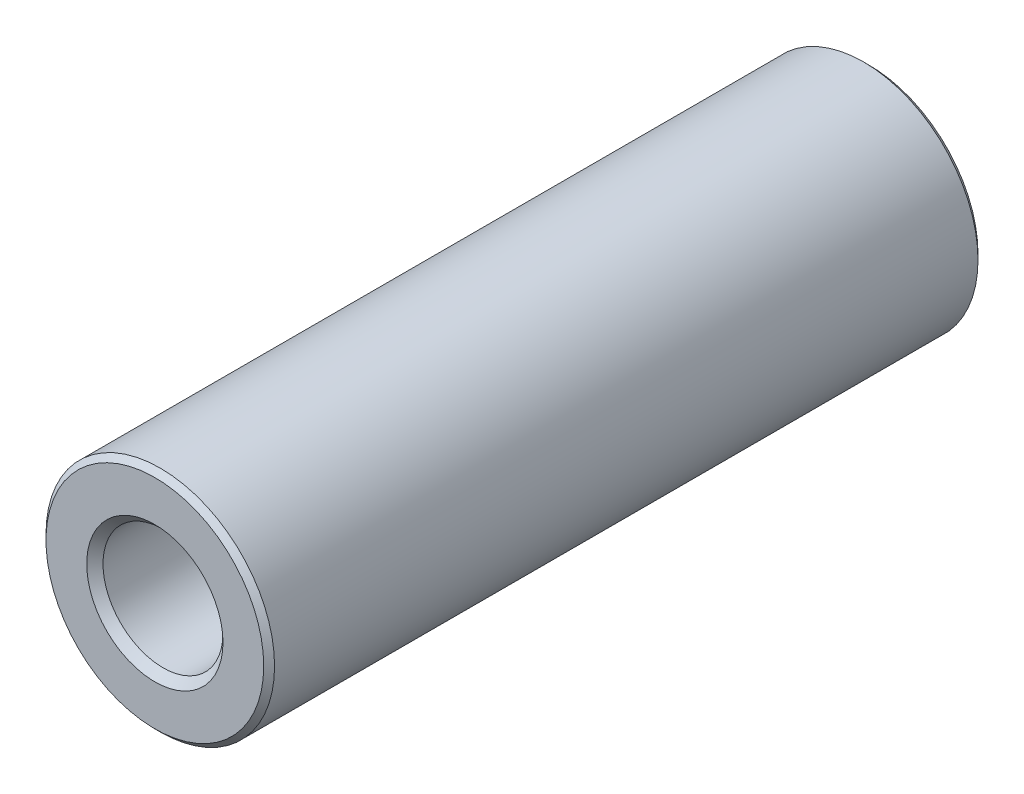
SolidWorks part; units mm, degrees
ref_plane "Front Plane" through (0, 0, 0) normal (0, 0, 1) x (1, 0, 0)
ref_plane "Top Plane" through (0, 0, 0) normal (0, 1, 0) x (1, 0, 0)
ref_plane "Right Plane" through (0, 0, 0) normal (1, 0, 0) x (0, 0, -1)
sketch "Sketch1" plane through (0, 0, 0) normal (0, 0, 1) x (1, 0, 0)
  circle A0 centre (0, 0) radius 4 construction
  circle A1 centre (0, 0) radius 2.1 construction
  point P4 (0, 4)
  dimension "ID" = 4.2
  dimension "OD" = 8
sketch "Sketch2" plane through (0, 0, 0) normal (1, 0, 0) x (0, 0, -1)
  line L0 (-12.5, 4) -> (12.5, 4) construction
  dimension "Length" = 25
sketch "Sketch3" plane through (0, 0, 0) normal (0, 0, 1) x (1, 0, 0)
  circle A0 centre (0, 0) radius 2.1 construction
  circle A1 centre (0, 0) radius 4 construction
  circle A2 centre (0, 0) radius 2.1
  circle A3 centre (0, 0) radius 4
extrude "Boss-Extrude1" add sketch "Sketch3" against normal up to vertex (12.5 mm away) and the other way up to vertex (12.5 mm away) up to point (0, 4, -12.5) other way up to point (0, 4, 12.5)
chamfer "Chamfer1" distance 0.19 angle 45 2 edges at (4, 0, 12.5) (4, 0, -12.5)
chamfer "Chamfer2" distance 0.285 angle 45 2 edges at (2.1, 0, 12.5) (2.1, 0, -12.5)
equation "\"D1@Chamfer1\"=(\"OD@Sketch1\"-\"ID@Sketch1\")*0.05"
equation "\"D1@Chamfer2\"=(\"OD@Sketch1\"-\"ID@Sketch1\")*0.075"
